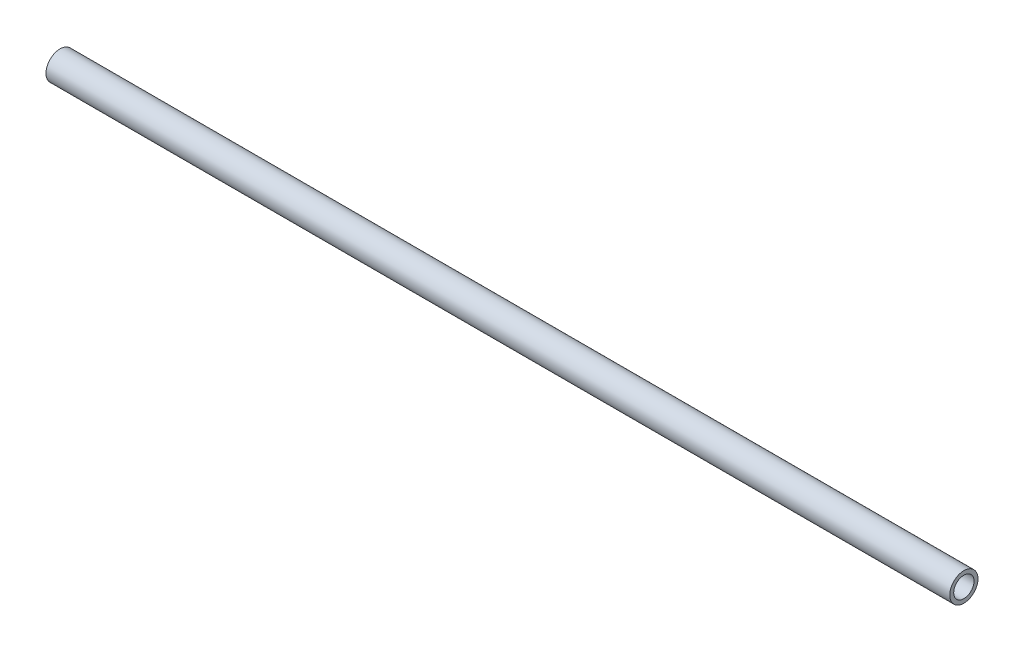
SolidWorks part; units mm, degrees
ref_plane "Front" through (0, 0, 0) normal (0, 0, 1) x (1, 0, 0)
ref_plane "Top" through (0, 0, 0) normal (0, 1, 0) x (1, 0, 0)
ref_plane "Right" through (0, 0, 0) normal (1, 0, 0) x (0, 0, -1)
sketch "Sketch1" plane through (0, 0, 0) normal (1, 0, 0) x (0, 0, -1)
  circle A0 centre (0, 0) radius 3.175
  circle A1 centre (0, 0) radius 2.286
  point P4 (3.175, 0)
  point P5 (2.286, 0)
  dimension "OD" = 6.35
  dimension "ID" = 4.572
  dimension "Wall" = 0.889
sketch "Sketch4" plane through (0, 0, 0) normal (1, 0, 0) x (0, 0, -1)
  circle A0 centre (0, 0) radius 3.175 construction
  circle A1 centre (0, 0) radius 3.175
  circle A2 centre (0, 0) radius 2.286 construction
  circle A3 centre (0, 0) radius 2.286
extrude "Boss-Extrude1" add sketch "Sketch4" along normal mid plane 203.2
sketch "Sketch2" plane through (0, 0, 0) normal (0, 0, 1) x (1, 0, 0)
  line L0 (-101.6, 0) -> (101.6, 0) construction
  line L2 (-101.6, 3.175) -> (-101.6, -3.175) construction
  point P5 (-73.0956, 0)
  point P6 (73.0956, 0)
  dimension "D1" = 28.5044
  dimension "D2" = 28.5044
equation "\"D1@Sketch2\"=.9+(\"length@Boss-Extrude1\"/36)"
equation "\"D2@Sketch2\"=\"D1@Sketch2\""
